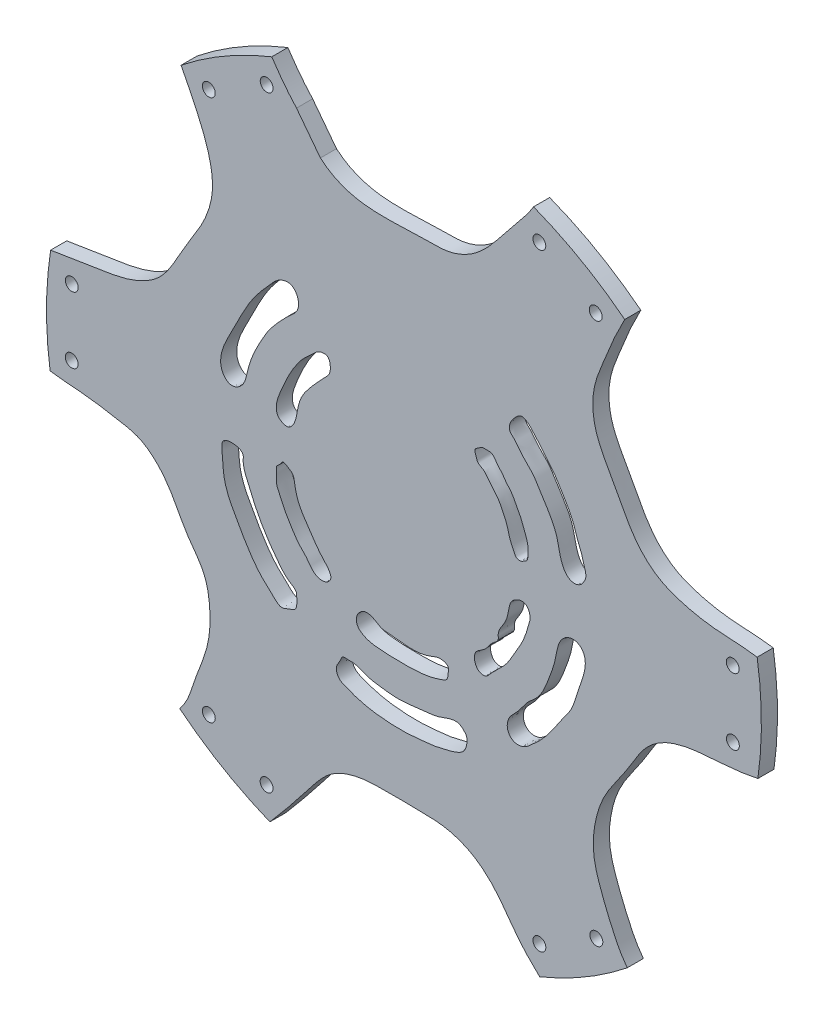
SolidWorks part; units mm, degrees
ref_plane "Front Plane" through (0, 0, 0) normal (0, 0, 1) x (1, 0, 0)
ref_plane "Top Plane" through (0, 0, 0) normal (0, 1, 0) x (1, 0, 0)
ref_plane "Right Plane" through (0, 0, 0) normal (1, 0, 0) x (0, 0, -1)
sketch "Sketch1" plane through (0, 0, 0) normal (0, 0, 1) x (1, 0, 0)
  circle A0 centre (0, 0) radius 222
extrude "Boss-Extrude1" add sketch "Sketch1" along normal blind 10
sketch "Sketch9" plane through (0, 0, 10) normal (0, 0, 1) x (1, 0, 0)
  spline S0 degree 2 poles (-86.1499, 212.8609) (-77.8812, 198.5912) (-66.7212, 186.3672) knots 0 0 0 1 1 1
  spline S1 degree 1 poles (-51.8847, 166.9384) (-66.7212, 186.3672) knots 0 0 1 1
  spline S2 degree 3 poles (-51.8847, 166.9384) (-44.8493, 160.7879) (-31.1568, 155.5408) (-8.0556, 154.5594) (10.0004, 155.828) (27.7625, 155.5382) (40.6134, 160.5968) (53.3151, 171.1924) (63.8758, 185.9772) (116.0099, 243.7336) (99.1213, 350.4098) (-86.1499, 212.8609) knots 0 0 0 0 0.079562 0.125021 0.201325 0.238489 0.279266 0.318866 0.381819 0.43751 1 1 1 1
extrude "Cut-Extrude14" cut sketch "Sketch9" against normal blind 10
sketch "Sketch10" plane through (0, 0, 0) normal (0, 0, 1) x (1, 0, 0)
  arc A0 (-82.1, 206.261) -> (80.5035, 206.8893) centre (0, 0) ccw construction
  spline S0 degree 3 poles (205.4246, 206.5301) (151.9911, 200.5433) (137.803, 176.3021) (130.133, 160.8322) (124.2105, 145.6304) (118.2113, 131.9746) (116.8706, 118.1893) (118.4851, 106.6415) (123.6278, 94.5174) (130.8002, 82.8206) (137.301, 69.4734) (145.5778, 56.1291) (157.7557, 45.1619) (175.0418, 38.9845) (192.672, 35.7925) (217.4588, 35.3933) (267.401, 23.7403) (269.6182, 111.7929) (224.1873, 148.0149) (205.4246, 206.5301) (151.9911, 200.5433) (137.803, 176.3021) knots -0.322338 -0.205001 -0.094164 0 0.043066 0.074446 0.106599 0.143487 0.165327 0.190939 0.214345 0.245796 0.275284 0.305623 0.342081 0.373289 0.417478 0.450871 0.529832 0.677662 0.794999 0.905836 1 1.043066 1.074446 1.106599 only from (149.4652, 191.58) to (149.4652, 191.58)
extrude "Cut-Extrude16" cut sketch "Sketch10" along normal blind 10
sketch "Sketch11" plane through (0, 0, 0) normal (0, 0, 1) x (1, 0, 0)
  arc A0 (-82.1, 206.261) -> (219.3657, 34.0982) centre (0, 0) ccw construction
  spline S0 degree 3 poles (276.2537, -61.7391) (267.208, -14.6865) (223.1091, -32.8815) (191.1722, -34.1093) (166.5613, -36.8245) (148.2286, -49.085) (138.5151, -68.7752) (124.4213, -85.5329) (118.198, -105.0963) (116.5541, -122.7073) (122.5574, -140.7281) (128.9953, -156.4093) (135.5954, -170.001) (159.6955, -198.5799) (204.5857, -130.2707) (277.6278, -119.5104) (276.2537, -61.7391) (267.208, -14.6865) (223.1091, -32.8815) knots -0.303166 -0.163663 -0.039808 0 0.096595 0.159064 0.214829 0.241442 0.29077 0.3462 0.374037 0.415495 0.452013 0.489121 0.519051 0.546468 0.696834 0.836337 0.960192 1 1.096595 1.159064 1.214829 only from (267.0093, -28.1164) to (267.0093, -28.1164)
extrude "Cut-Extrude18" cut sketch "Sketch11" along normal blind 10
sketch "Sketch12" plane through (0, 0, 0) normal (0, 0, 1) x (1, 0, 0)
  spline S0 degree 3 poles (86.5328, -245.2089) (101.6704, -218.5504) (75.1136, -199.5286) (61.7545, -177.4654) (45.7362, -160.4891) (28.4422, -154.028) (9.1213, -153.2501) (-7.6198, -153.149) (-27.7994, -153.2812) (-45.7803, -159.2632) (-57.9429, -174.501) (-68.8629, -188.9269) (-80.5876, -202.3213) (-90.9845, -215.5717) (-110.19, -256.9758) (-7.547, -255.1683) (40.4654, -247.8181) (86.5328, -245.2089) (101.6704, -218.5504) (75.1136, -199.5286) knots -0.252311 -0.098783 -0.018734 0 0.082182 0.133318 0.175937 0.227543 0.246618 0.299912 0.334856 0.376215 0.415701 0.456821 0.493292 0.528694 0.568278 0.747689 0.901217 0.981266 1 1.082182 1.133318 1.175937 only from (95.4647, -227.9744) to (95.4647, -227.9744)
extrude "Cut-Extrude19" cut sketch "Sketch12" along normal blind 10
sketch "Sketch13" plane through (0, 0, 0) normal (0, 0, 1) x (1, 0, 0)
  arc A0 (-82.1, 206.261) -> (-83.2318, -205.8069) centre (0, 0) ccw construction
  spline S0 degree 3 poles (-257.6931, -76.01) (-271.6478, -17.7172) (-225.8942, -32.3244) (-198.8978, -33.0423) (-180.1786, -36.146) (-163.3561, -39.3237) (-151.6911, -48.617) (-142.3862, -62.1708) (-135.1156, -77.6358) (-123.2939, -91.168) (-119.7312, -110.671) (-120.8157, -131.171) (-129.4144, -149.8752) (-135.8207, -173.9022) (-182.2809, -204.4018) (-266.4614, -209.0421) (-308.534, -115.7324) (-257.6931, -76.01) (-271.6478, -17.7172) (-225.8942, -32.3244) knots -0.296183 -0.178497 -0.039607 0 0.082528 0.11977 0.162164 0.183826 0.212717 0.240523 0.273563 0.306088 0.336415 0.379241 0.416332 0.448782 0.51173 0.703817 0.821503 0.960393 1 1.082528 1.11977 1.162164 only from (-264.9793, -31.348) to (-264.9793, -31.348)
extrude "Cut-Extrude20" cut sketch "Sketch13" along normal blind 10
sketch "Sketch14" plane through (0, 0, 0) normal (0, 0, 1) x (1, 0, 0)
  arc A0 (-82.1, 206.261) -> (-219.7517, -31.5148) centre (0, 0) ccw construction
  spline S0 degree 3 poles (-224.3449, 200.1296) (-169.7507, 234.9411) (-143.5184, 183.483) (-128.7699, 154.7468) (-120.7443, 135.612) (-117.4613, 114.5325) (-123.9035, 95.6826) (-133.8061, 81.3028) (-141.8525, 66.6131) (-150.8879, 51.2767) (-169.8387, 41.2893) (-193.4949, 37.7692) (-225.4408, 32.4177) (-284.6672, 24.8732) (-277.9223, 105.2345) (-283.2696, 173.4932) (-224.3449, 200.1296) (-169.7507, 234.9411) (-143.5184, 183.483) knots -0.336878 -0.181019 -0.101146 0 0.102572 0.139206 0.181223 0.213227 0.252267 0.284973 0.307584 0.343121 0.378719 0.418873 0.470527 0.564608 0.663122 0.818981 0.898854 1 1.102572 1.139206 1.181223 only from (-174.2121, 217.85) to (-174.2121, 217.85)
extrude "Cut-Extrude21" cut sketch "Sketch14" along normal blind 10
sketch "Sketch15" plane through (0, 0, 0) normal (0, 0, 1) x (1, 0, 0)
  spline S0 degree 3 poles (68.676, 87.5316) (73.7672, 92.5639) (81.198, 84.9451) (86.6444, 77.905) (93.8346, 69.9188) (98.621, 61.4825) (103.5989, 53.4921) (106.1851, 46.7393) (108.1194, 40.3862) (110.6048, 34.9049) (112.0434, 29.2587) (113.408, 24.3493) (111.964, 20.9461) (109.9238, 17.9401) (105.8277, 16.4597) (101.1694, 18.3443) (98.2167, 23.2095) (96.334, 29.7268) (95.2205, 36.7724) (92.321, 43.4322) (88.6327, 49.7425) (84.2907, 56.4064) (79.648, 64.2773) (73.0081, 69.5895) (69.3495, 75.6539) (64.7248, 79.0489) (66.0548, 84.2521) (68.676, 87.5316) (73.7672, 92.5639) (81.198, 84.9451) knots -0.073693 -0.051901 -0.024245 0 0.051878 0.106561 0.163713 0.225316 0.268455 0.319785 0.344863 0.378943 0.419092 0.443124 0.459965 0.478546 0.502551 0.52549 0.556307 0.593208 0.638552 0.674106 0.71317 0.760003 0.806506 0.864205 0.897292 0.926307 0.948099 0.975755 1 1.051878 1.106561 1.163713 only from (72.4714, 90.3998) to (72.4714, 90.3998)
extrude "Cut-Extrude22" cut sketch "Sketch15" along normal blind 10
sketch "Sketch16" plane through (0, 0, 0) normal (0, 0, 1) x (1, 0, 0)
  spline S0 degree 3 poles (51.5372, 61.4617) (55.5909, 61.868) (57.5823, 56.692) (61.26, 53.9324) (62.7367, 51.0357) (64.9812, 48.5103) (67.3753, 45.7846) (69.1836, 42.199) (70.7774, 38.7821) (73.0548, 35.1659) (74.0135, 31.3945) (75.6819, 27.9155) (76.5753, 24.7909) (77.3649, 21.1651) (77.0085, 17.8772) (76.8394, 14.4153) (74.7414, 13.5572) (73.3631, 12.4947) (71.4451, 12.0819) (69.1403, 13.0122) (68.2474, 15.5414) (66.7433, 18.3869) (65.402, 21.8838) (64.502, 26.0893) (62.944, 30.6217) (60.7063, 34.9484) (58.4194, 39.2473) (55.2752, 42.8471) (52.1948, 46.3048) (49.7015, 50.2011) (45.6457, 51.4437) (44.9523, 54.9997) (43.2662, 58.3426) (46.5189, 60.1642) (48.9514, 61.9789) (51.5372, 61.4617) (55.5909, 61.868) (57.5823, 56.692) knots -0.059437 -0.03557 -0.011116 0 0.058955 0.089619 0.112127 0.135043 0.17063 0.198486 0.230798 0.261138 0.30017 0.323086 0.353324 0.37818 0.410434 0.435782 0.450275 0.460762 0.477765 0.494696 0.515102 0.538472 0.572948 0.603953 0.641566 0.687303 0.720669 0.757819 0.801228 0.831972 0.867123 0.888591 0.916931 0.940563 0.96443 0.988884 1 1.058955 1.089619 1.112127 only from (53.4986, 61.5642) to (53.4986, 61.5642)
extrude "Cut-Extrude23" cut sketch "Sketch16" along normal blind 10
sketch "Sketch17" plane through (0, 0, 10) normal (0, 0, 1) x (1, 0, 0)
  spline S0 degree 3 poles (-69.056, 90.3738) (-77.6973, 89.7778) (-84.1841, 81.9759) (-92.6991, 72.6398) (-100.2093, 59.9188) (-106.731, 46.2369) (-113.2395, 34.4651) (-114.4532, 24.4527) (-111.3662, 18.738) (-106.153, 16.0378) (-98.8626, 20.5231) (-97.2753, 29.8921) (-94.319, 39.5493) (-89.485, 48.9221) (-84.6065, 57.9479) (-77.8742, 65.6856) (-71.9372, 72.0594) (-65.4035, 77.2223) (-65.1584, 84.5276) (-69.056, 90.3738) (-77.6973, 89.7778) (-84.1841, 81.9759) knots -0.101213 -0.065122 -0.029467 0 0.062479 0.129438 0.211767 0.304383 0.380687 0.434228 0.461867 0.483154 0.52393 0.578256 0.635587 0.691486 0.752128 0.804922 0.859721 0.898787 0.934878 0.970533 1 1.062479 1.129438 1.211767 only from (-75.2077, 89.5124) to (-75.2077, 89.5124)
extrude "Cut-Extrude26" cut sketch "Sketch17" against normal blind 10
sketch "Sketch18" plane through (0, 0, 10) normal (0, 0, 1) x (1, 0, 0)
  spline S0 degree 3 poles (-46.7412, 63.4921) (-53.2467, 62.7931) (-57.4282, 58.352) (-62.7417, 53.8167) (-67.0648, 48.0052) (-70.8946, 41.7896) (-73.9773, 35.3218) (-77.2111, 27.8615) (-79.7127, 21.2415) (-78.7947, 14.0231) (-71.5394, 10.4429) (-67.4405, 16.93) (-66.2424, 23.3209) (-64.639, 32.1822) (-58.7865, 39.7968) (-53.259, 45.9513) (-49.2952, 50.1058) (-45.8321, 53.5029) (-45.5161, 58.0642) (-46.7412, 63.4921) (-53.2467, 62.7931) (-57.4282, 58.352) knots -0.110637 -0.076182 -0.040322 0 0.044699 0.105714 0.163813 0.215136 0.278266 0.332697 0.408391 0.441518 0.497861 0.544064 0.593585 0.65749 0.751832 0.815005 0.853153 0.889363 0.923818 0.959678 1 1.044699 1.105714 1.163813 only from (-52.5296, 62.3474) to (-52.5296, 62.3474)
extrude "Cut-Extrude27" cut sketch "Sketch18" against normal blind 10
sketch "Sketch19" plane through (0, 0, 10) normal (0, 0, 1) x (1, 0, 0)
  spline S0 degree 3 poles (-99.3411, -14.9091) (-100.315, -22.6279) (-96.6619, -30.2904) (-92.3077, -41.1166) (-86.3083, -52.1234) (-78.9241, -62.4737) (-72.7811, -70.0378) (-66.3994, -73.2448) (-66.6131, -76.9778) (-66.4141, -80.0243) (-66.9873, -84.288) (-71.6287, -85.1412) (-76.7957, -88.2513) (-82.4566, -81.8465) (-89.4766, -75.994) (-96.8746, -65.7878) (-103.9851, -53.3162) (-111.9979, -38.6267) (-112.5539, -26.3667) (-113.5867, -14.6982) (-106.2787, -13.0357) (-99.3411, -14.9091) (-100.315, -22.6279) (-96.6619, -30.2904) knots -0.084485 -0.055518 -0.011671 0 0.064422 0.123493 0.192449 0.269258 0.330077 0.356219 0.371914 0.386021 0.408869 0.431521 0.45606 0.499476 0.544469 0.61507 0.699659 0.783976 0.878995 0.915515 0.944482 0.988329 1 1.064422 1.123493 1.192449 only from (-99.8238, -19.2194) to (-99.8238, -19.2194)
extrude "Cut-Extrude28" cut sketch "Sketch19" against normal blind 10
sketch "Sketch20" plane through (0, 0, 0) normal (0, 0, 1) x (1, 0, 0)
  spline S0 degree 3 poles (-79.5866, -12.1644) (-78.6469, -16.6583) (-79.8981, -21.7004) (-76.5895, -27.6608) (-74.1956, -33.6572) (-70.203, -39.9881) (-65.9895, -47.0203) (-59.9295, -52.3724) (-56.266, -58.7416) (-50.4518, -60.383) (-46.6598, -58.6852) (-44.7547, -55.4682) (-46.6074, -51.6967) (-49.8498, -48.2192) (-53.7305, -43.8783) (-57.3287, -38.1532) (-61.9313, -31.9166) (-66.1904, -24.4817) (-67.7456, -17.4782) (-68.5094, -11.5423) (-71.7365, -9.7126) (-75.3686, -7.1469) (-76.8473, -10.805) (-79.5866, -12.1644) (-78.6469, -16.6583) (-79.8981, -21.7004) knots -0.063603 -0.038215 -0.01793 0 0.056486 0.101933 0.151272 0.208317 0.275452 0.340822 0.395471 0.440697 0.465557 0.488023 0.519207 0.552953 0.601281 0.6535 0.710199 0.782393 0.848926 0.881559 0.91026 0.936397 0.961785 0.98207 1 1.056486 1.101933 1.151272 only from (-79.1175, -14.8054) to (-79.1175, -14.8054)
extrude "Cut-Extrude30" cut sketch "Sketch20" along normal blind 10
sketch "Sketch21" plane through (0, 0, 0) normal (0, 0, 1) x (1, 0, 0)
  spline S0 degree 3 poles (-29.7218, -67.9274) (-29.7422, -73.6361) (-23.2307, -77.8989) (-15.6593, -78.8721) (-5.7602, -79.3532) (4.7446, -79.4274) (15.3236, -78.5925) (22.0054, -76.4752) (27.366, -74.661) (27.2141, -70.7155) (28.5211, -66.29) (22.2362, -64.3803) (17.8513, -66.4054) (12.4186, -68.2732) (5.8344, -69.0435) (-1.9872, -68.3997) (-8.3654, -67.6141) (-14.3619, -67.2897) (-18.3623, -64.1196) (-23.5335, -62.4397) (-27.2851, -64.7608) (-29.7218, -67.9274) (-29.7422, -73.6361) (-23.2307, -77.8989) knots -0.090917 -0.062121 -0.040785 0 0.051216 0.120129 0.176687 0.278649 0.363877 0.414513 0.448952 0.474488 0.49807 0.544418 0.578677 0.613401 0.675079 0.730071 0.79313 0.824854 0.864164 0.909083 0.937879 0.959215 1 1.051216 1.120129 1.176687 only from (-29.0054, -72.679) to (-29.0054, -72.679)
extrude "Cut-Extrude32" cut sketch "Sketch21" along normal blind 10
sketch "Sketch22" plane through (0, 0, 10) normal (0, 0, 1) x (1, 0, 0)
  spline S0 degree 3 poles (-34.8109, -94.5292) (-29.9948, -93.9194) (-23.1394, -97.7904) (-14.1306, -98.804) (-4.9454, -100.1228) (4.5652, -99.2601) (13.5004, -98.2062) (22.1232, -97.1984) (28.0527, -94.2358) (34.0697, -93.6386) (36.9296, -96.1206) (39.3935, -98.8108) (39.1697, -103.1324) (37.5509, -108.1253) (31.6618, -111.0735) (24.8983, -112.5927) (18.0955, -114.2434) (11.5873, -114.6936) (2.5793, -115.8209) (-10.229, -115.6365) (-24.1014, -113.9363) (-34.1182, -110.475) (-41.1597, -107.665) (-42.6929, -101.3205) (-39.5862, -98.0245) (-38.454, -93.682) (-34.8109, -94.5292) (-29.9948, -93.9194) (-23.1394, -97.7904) knots -0.052337 -0.03151 -0.016682 0 0.049537 0.103338 0.148986 0.20096 0.258785 0.297333 0.341294 0.368171 0.388748 0.400617 0.426633 0.453653 0.483223 0.527524 0.569147 0.597089 0.634345 0.717755 0.80675 0.860383 0.89408 0.924438 0.947663 0.96849 0.983318 1 1.049537 1.103338 1.148986 only from (-31.9569, -94.3338) to (-31.9569, -94.3338)
extrude "Cut-Extrude33" cut sketch "Sketch22" against normal blind 10
sketch "Sketch23" plane through (0, 0, 0) normal (0, 0, 1) x (1, 0, 0)
  spline S0 degree 3 poles (59.0001, -37.9081) (57.9057, -31.394) (63.6596, -25.9425) (64.8415, -18.3103) (66.0427, -12.5227) (69.9475, -9.2538) (75.6324, -8.1011) (79.2467, -14.1707) (77.4508, -19.6751) (75.7837, -25.2352) (73.6434, -31.0067) (69.1576, -37.9289) (65.0591, -46.1522) (58.8806, -52.7148) (54.1463, -56.9234) (50.8884, -61.0978) (46.3555, -60.3441) (43.6051, -56.3157) (43.502, -49.8878) (48.8702, -47.6222) (52.2416, -44.099) (54.5092, -40.2413) (59.0001, -37.9081) (57.9057, -31.394) (63.6596, -25.9425) knots -0.095689 -0.05742 -0.016707 0 0.083885 0.141522 0.178509 0.215357 0.254516 0.293144 0.351168 0.382286 0.428135 0.492145 0.572054 0.639114 0.69687 0.721845 0.75362 0.784066 0.830512 0.878058 0.904311 0.94258 0.983293 1 1.083885 1.141522 1.178509 only from (58.5484, -34.5232) to (58.5484, -34.5232)
extrude "Cut-Extrude35" cut sketch "Sketch23" along normal blind 10
sketch "Sketch24" plane through (0, 0, 0) normal (0, 0, 1) x (1, 0, 0)
  spline S0 degree 3 poles (75.9023, -61.6301) (85.1783, -54.6664) (89.7589, -42.9064) (94.4777, -30.1949) (95.4395, -19.8892) (100.7032, -13.781) (107.3189, -12.9034) (112.2971, -17.3763) (113.1535, -25.3908) (109.8716, -34.204) (106.8563, -43.8736) (103.6804, -53.2586) (97.5505, -60.4173) (92.189, -69.1226) (85.982, -77.018) (79.4207, -82.9382) (74.11, -87.4581) (67.6879, -87.5463) (63.6571, -82.5449) (64.4443, -75.1139) (71.7282, -69.2759) (75.9023, -61.6301) (85.1783, -54.6664) (89.7589, -42.9064) knots -0.139343 -0.0921 -0.028248 0 0.093735 0.166972 0.223142 0.256841 0.290246 0.31933 0.355404 0.413719 0.470831 0.521035 0.572685 0.622161 0.687571 0.734605 0.766565 0.798716 0.826238 0.860657 0.9079 0.971752 1 1.093735 1.166972 1.223142 only from (81.7365, -56.9714) to (81.7365, -56.9714)
extrude "Cut-Extrude37" cut sketch "Sketch24" along normal blind 10
sketch "Sketch25" plane through (0, 0, 0) normal (0, 0, 1) x (1, 0, 0)
  circle A0 centre (-121.2106, 169.0903) radius 4
extrude "Cut-Extrude39" cut sketch "Sketch25" along normal blind 10
sketch "Sketch26" plane through (0, 0, 10) normal (0, 0, 1) x (1, 0, 0)
  circle A0 centre (-85.2537, 189.6445) radius 4
extrude "Cut-Extrude40" cut sketch "Sketch26" against normal blind 10
sketch "Sketch27" plane through (0, 0, 10) normal (0, 0, 1) x (1, 0, 0)
  circle A0 centre (119.1342, 169.0199) radius 4
extrude "Cut-Extrude41" cut sketch "Sketch27" against normal blind 10
sketch "Sketch28" plane through (0, 0, 10) normal (0, 0, 1) x (1, 0, 0)
  circle A0 centre (84.0959, 189.5902) radius 4
extrude "Cut-Extrude42" cut sketch "Sketch28" against normal blind 10
sketch "Sketch29" plane through (0, 0, 10) normal (0, 0, 1) x (1, 0, 0)
  circle A0 centre (204.1926, 22.0351) radius 4
extrude "Cut-Extrude43" cut sketch "Sketch29" against normal blind 10
sketch "Sketch30" plane through (0, 0, 10) normal (0, 0, 1) x (1, 0, 0)
  circle A0 centre (204.2937, -19.1847) radius 4
extrude "Cut-Extrude44" cut sketch "Sketch30" against normal blind 10
sketch "Sketch31" plane through (0, 0, 0) normal (0, 0, 1) x (1, 0, 0)
  circle A0 centre (119.5145, -167.1842) radius 4
extrude "Cut-Extrude46" cut sketch "Sketch31" along normal blind 10
sketch "Sketch32" plane through (0, 0, 10) normal (0, 0, 1) x (1, 0, 0)
  circle A0 centre (84.1304, -187.7117) radius 4
extrude "Cut-Extrude47" cut sketch "Sketch32" against normal blind 10
sketch "Sketch33" plane through (0, 0, 0) normal (0, 0, 1) x (1, 0, 0)
  circle A0 centre (-85.3041, -186.893) radius 4
extrude "Cut-Extrude49" cut sketch "Sketch33" along normal blind 10
sketch "Sketch34" plane through (0, 0, 10) normal (0, 0, 1) x (1, 0, 0)
  circle A0 centre (-121.1827, -167.0964) radius 4
extrude "Cut-Extrude50" cut sketch "Sketch34" against normal blind 10
sketch "Sketch35" plane through (0, 0, 10) normal (0, 0, 1) x (1, 0, 0)
  circle A0 centre (-206.3409, -19.2082) radius 4
extrude "Cut-Extrude51" cut sketch "Sketch35" against normal blind 10
sketch "Sketch36" plane through (0, 0, 10) normal (0, 0, 1) x (1, 0, 0)
  circle A0 centre (-206.2994, 21.958) radius 4
extrude "Cut-Extrude52" cut sketch "Sketch36" against normal blind 10
